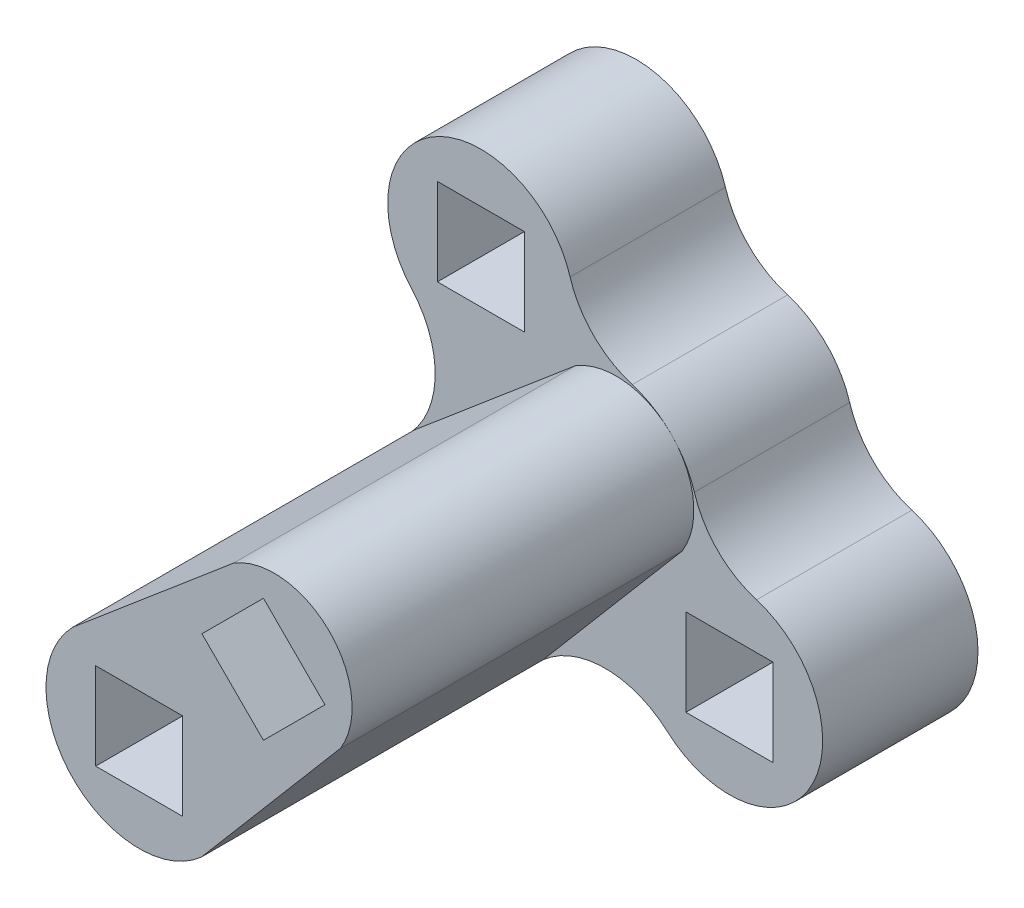
SolidWorks part; units mm, degrees
ref_plane "Plano frontal" through (0, 0, 0) normal (0, 0, 1) x (1, 0, 0)
ref_plane "Plano superior" through (0, 0, 0) normal (0, 1, 0) x (1, 0, 0)
ref_plane "Plano direito" through (0, 0, 0) normal (1, 0, 0) x (0, 0, -1)
sketch "Esboço1" plane through (0, 0, 0) normal (0, 0, 1) x (1, 0, 0)
  line L0 (0, 0) -> (0, 8) construction
  line L1 (0, 0) -> (8, 0) construction
  line L2 (8, 0) -> (0, 8) construction
  line L3 (1.4, 9.4) -> (1.4, 6.6)
  line L10 (-1.4, 9.4) -> (-1.4, 6.6)
  line L11 (-1.4, 6.6) -> (1.4, 6.6)
  line L12 (-1.4, 9.4) -> (1.4, 6.6) construction
  line L13 (-1.4, 6.6) -> (1.4, 9.4) construction
  line L14 (-1.4, 9.4) -> (1.4, 9.4)
  line L15 (4, 5.9799) -> (5.9799, 4)
  line L16 (2.0201, 4) -> (4, 2.0201)
  line L17 (4, 2.0201) -> (5.9799, 4)
  line L18 (2.0201, 4) -> (5.9799, 4) construction
  line L19 (4, 2.0201) -> (4, 5.9799) construction
  line L20 (2.0201, 4) -> (4, 5.9799)
  line L21 (9.4, 1.4) -> (9.4, -1.4)
  line L22 (6.6, 1.4) -> (6.6, -1.4)
  line L23 (6.6, -1.4) -> (9.4, -1.4)
  line L24 (6.6, 1.4) -> (9.4, -1.4) construction
  line L25 (6.6, -1.4) -> (9.4, 1.4) construction
  line L26 (6.6, 1.4) -> (9.4, 1.4)
  line L27 (1.4, 1.4) -> (1.4, -1.4)
  line L28 (-1.4, 1.4) -> (-1.4, -1.4)
  line L29 (-1.4, -1.4) -> (1.4, -1.4)
  line L30 (-1.4, 1.4) -> (1.4, -1.4) construction
  line L31 (-1.4, -1.4) -> (1.4, 1.4) construction
  line L32 (-1.4, 1.4) -> (1.4, 1.4)
  arc A0 (2.8708, 8.8708) -> (-2.2361, 6) centre (0, 8) ccw
  arc A1 (-2.2361, 2) -> (2, -2.2361) centre (0, 0) ccw
  arc A3 (6.8708, 4.8708) -> (4.8708, 6.8708) centre (4, 4) ccw
  arc A4 (-2.2361, 2) -> (-2.2361, 6) centre (-4.4721, 4) ccw
  arc A5 (2.8708, 8.8708) -> (4.8708, 6.8708) centre (5.7417, 9.7417) ccw
  arc A6 (6.8708, 4.8708) -> (8.8708, 2.8708) centre (9.7417, 5.7417) ccw
  arc A7 (6, -2.2361) -> (2, -2.2361) centre (4, -4.4721) ccw
  arc A9 (6, -2.2361) -> (8.8708, 2.8708) centre (8, 0) ccw
  point P2 (4, 4)
  point P9 (0, 8)
  point P14 (4, 4)
  point P19 (8, 0)
  point P24 (0, 0)
  dimension "D3" = 6
  dimension "D8" = 6
  dimension "D1" = 8
  dimension "D2" = 8
  dimension "D4" = 2.8
  dimension "D5" = 2.8
  dimension "D6" = 2.8
  dimension "D7" = 2.8
extrude "Ressalto-extrusão1" add sketch "Esboço1" along normal blind 16
sketch "Esboço2" plane through (0, 0, 16) normal (0, 0, 1) x (1, 0, 0)
  line L0 (3.0427, 6.4823) -> (-2.1448, 2.0976)
  line L1 (2, -2.2361) -> (6.476, 3.0325)
  arc A0 (6.476, 3.0325) -> (3.0427, 6.4823) centre (4.3536, 4.3536) ccw
  arc A1 (-2.1448, 2.0976) -> (2, -2.2361) centre (0, 0) ccw
  arc A2 (6.8708, 4.8708) -> (4.8708, 6.8708) centre (4, 4) ccw construction
  point P16 (4, 4)
  dimension "D1" = 5
  dimension "D2" = 3
extrude "Corte-Extrusão-Fina1" cut sketch "Esboço2" against normal blind 11 thin
